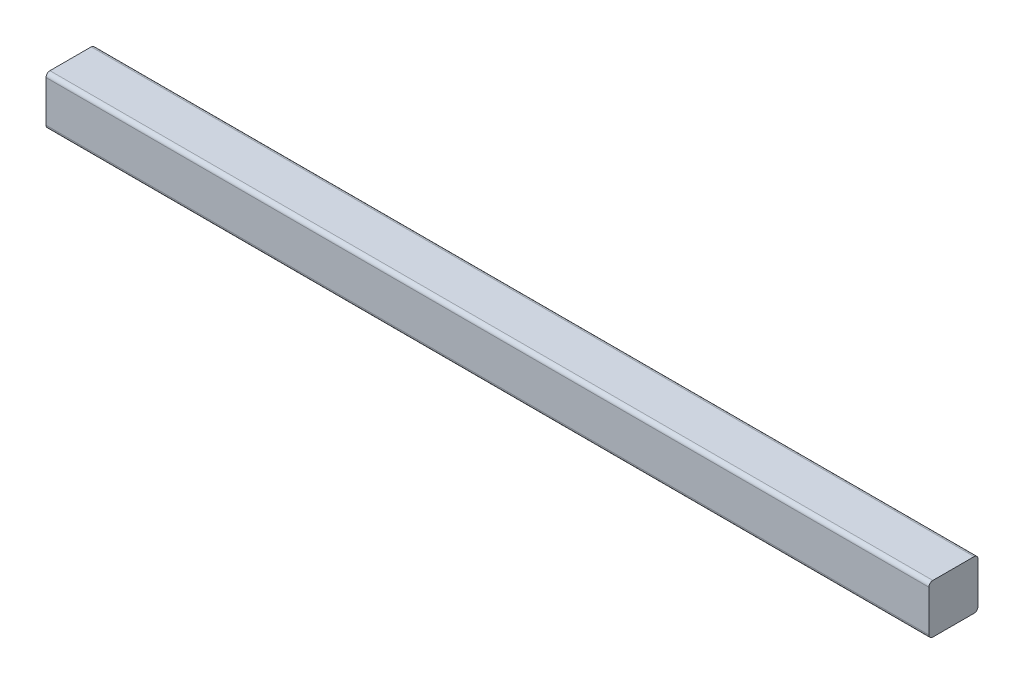
SolidWorks part; units mm, degrees
ref_plane "Front Plane" through (0, 0, 0) normal (0, 0, 1) x (1, 0, 0)
ref_plane "Top Plane" through (0, 0, 0) normal (0, 1, 0) x (1, 0, 0)
ref_plane "Right Plane" through (0, 0, 0) normal (1, 0, 0) x (0, 0, -1)
ref_plane "Plane1" through (45.439, 0, 0) normal (1, 0, 0) x (0, 0, -1)
sketch "Sketch1" plane through (0, 0, 0) normal (0, 0, 1) x (1, 0, 0)
  line L0 (45.439, -11.3436) -> (45.439, 11.3436) construction
  line L1 (-11.6529, -1.5875) -> (45.439, -1.5875)
  line L2 (-11.6529, -1.5875) -> (-11.6529, 1.5875)
  line L3 (-11.6529, 1.5875) -> (45.439, 1.5875)
  line L4 (45.439, -1.5875) -> (45.439, 1.5875)
  point P0 (0, 0)
  dimension "D1" = 3.175
  dimension "D2" = 1.5875
extrude "Boss-Extrude1" add sketch "Sketch1" along normal mid plane 3.175
fillet "Fillet1" radius 0.254 4 edges at (16.893, -1.5875, -1.5875) (16.893, -1.5875, 1.5875) (16.893, 1.5875, -1.5875) (16.893, 1.5875, 1.5875)
sketch "Sketch2" plane through (-11.6529, 0, 0) normal (-1, 0, 0) x (0, 0, 1)
  circle A0 centre (0, 0) radius 1.5875
  dimension "D1" = 3.175
